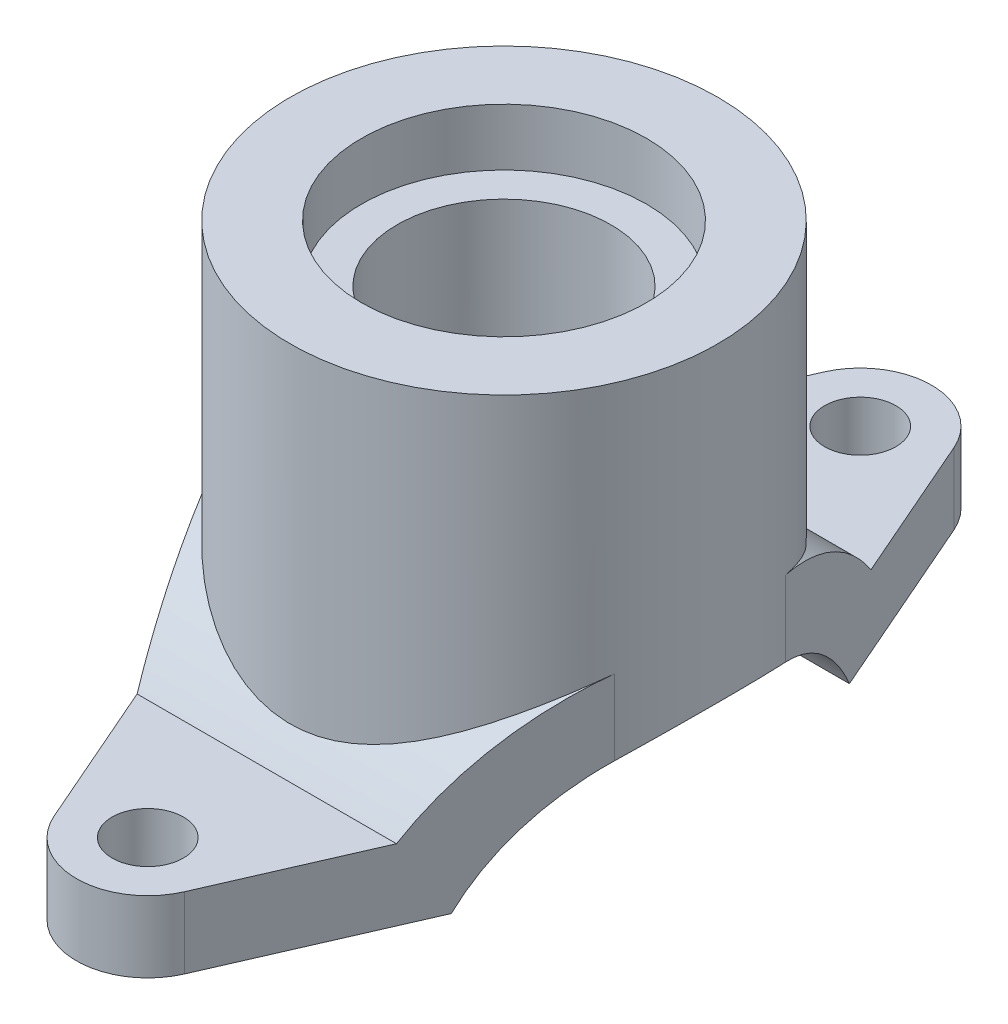
SolidWorks part; units mm, degrees
ref_plane "Front Plane" through (0, 0, 0) normal (0, 0, 1) x (1, 0, 0)
ref_plane "Top Plane" through (0, 0, 0) normal (0, 1, 0) x (1, 0, 0)
ref_plane "Right Plane" through (0, 0, 0) normal (1, 0, 0) x (0, 0, -1)
sketch "Sketch1" plane through (0, 0, 0) normal (1, 0, 0) x (0, 0, -1)
  line L0 (0, 1000) -> (0, 0) construction
  line L1 (1139.6997, 0) -> (69.8498, 0) construction
  line L2 (83.2406, 25) -> (150, 25)
  line L3 (-150, 25) -> (-83.2406, 25)
  line L4 (-150, 25) -> (-150, 0)
  line L5 (-150, 0) -> (-69.8498, 0)
  line L6 (150, 25) -> (150, 0)
  line L7 (0, 0) -> (0, 25) construction
  line L9 (-69.8498, 0) -> (-85798.3905, 0) construction
  line L10 (69.8498, 0) -> (150, 0)
  arc A0 (69.8498, 0) -> (-69.8498, 0) centre (0, -39) ccw
  arc A2 (83.2406, 25) -> (-83.2406, 25) centre (0, -39) ccw
  point P1 (150, 12.5)
  point P7 (-316.0393, 53.3891)
  point P8 (0, 12.5)
  dimension "D1" = 39
  dimension "D2" = 160
  dimension "D3" = 105
  dimension "D4" = 300
  dimension "D5" = 25
extrude "Boss-Extrude1" add sketch "Sketch1" against normal blind 150
sketch "Sketch2" plane through (0, 0, 0) normal (0, 1, 0) x (1, 0, 0)
  line L0 (0, -83.2406) -> (0, 83.2406) construction
  line L1 (1000, 0) -> (0, 0) construction
  line L2 (1000, 0) -> (0, 0) construction
  line L3 (0, 150) -> (0, 83.2406) construction
  line L4 (-143.7386, 30) -> (-97.9129, 135)
  line L5 (-75, -1000) -> (-75, 0) construction
  line L6 (-6.2614, 30) -> (-52.0871, 135)
  line L7 (-6.2614, -30) -> (-52.0871, -135)
  line L8 (-143.7386, -30) -> (-97.9129, -135)
  line L9 (-75, 100) -> (-75, 50000) construction
  line L10 (-150, 0) -> (-50000, 0) construction
  line L11 (-150, 0) -> (-50000, 0) construction
  arc A0 (-143.7386, 30) -> (-143.7386, -30) centre (-75, 0) ccw
  circle A1 centre (-75, 125) radius 12.5
  arc A2 (-52.0871, 135) -> (-97.9129, 135) centre (-75, 125) ccw
  arc A3 (-52.0871, -135) -> (-97.9129, -135) centre (-75, -125) cw
  circle A4 centre (-75, -125) radius 12.5
  arc A5 (-6.2614, -30) -> (-6.2614, 30) centre (-75, 0) ccw
  point P11 (-480.8097, -48.681)
  point P13 (-477.3235, 32.4989)
  dimension "D1" = 150
  dimension "D3" = 25
  dimension "D4" = 50
  dimension "D2" = 75
  dimension "D5" = 250
  dimension "D6" = 75
extrude "Cut-Extrude3" cut sketch "Sketch2" along normal blind 150 flip side to cut
ref_plane "Plane3" through (0, 150, 0) normal (0, -1, 0) x (-1, 0, 0)
sketch "Sketch5" plane through (0, 150, 0) normal (0, -1, 0) x (-1, 0, 0)
  circle A0 centre (75, 0) radius 37.5
  circle A1 centre (75, 0) radius 75
  dimension "D1" = 150
  dimension "D2" = 75
extrude "Boss-Extrude6" add sketch "Sketch5" along normal up to surface (90.9248 mm away)
sketch "Sketch6" plane through (0, 150, 0) normal (0, 1, 0) x (1, 0, 0)
  circle A0 centre (-75, 0) radius 50
  dimension "D1" = 100
extrude "Cut-Extrude4" cut sketch "Sketch6" against normal blind 20
